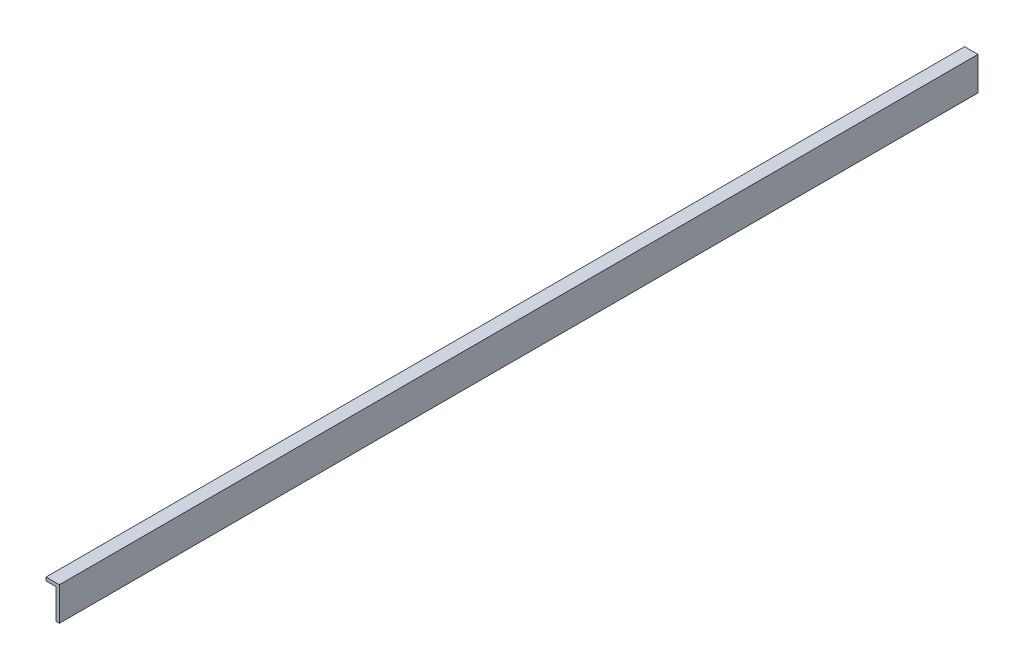
SolidWorks part; units mm, degrees
ref_plane "Front Plane" through (0, 0, 0) normal (0, 0, 1) x (1, 0, 0)
ref_plane "Top Plane" through (0, 0, 0) normal (0, 1, 0) x (1, 0, 0)
ref_plane "Right Plane" through (0, 0, 0) normal (1, 0, 0) x (0, 0, -1)
other "Configuration Table"
sketch "Sketch1" plane through (0, 0, 0) normal (0, 0, 1) x (1, 0, 0)
  line L0 (164, 870) -> (166, 870)
  line L1 (166, 870) -> (166, 890)
  line L2 (166, 890) -> (158, 890)
  line L3 (158, 890) -> (158, 888)
  line L4 (158, 888) -> (164, 888)
  line L5 (164, 888) -> (164, 870)
extrude "OVEN_yag_kabi_L_raf_sag_1" add sketch "Sketch1" against normal blind 550 from offset 30 separate body
